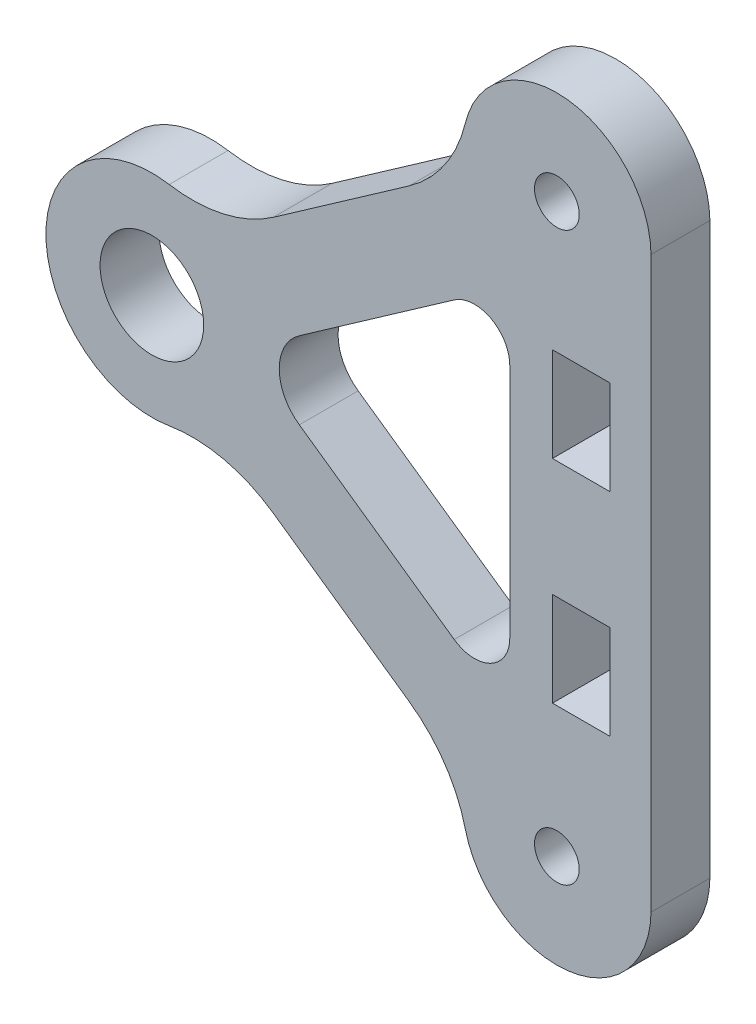
SolidWorks part; units mm, degrees
ref_plane "Plan de face" through (0, 0, 0) normal (0, 0, 1) x (1, 0, 0)
ref_plane "Plan de dessus" through (0, 0, 0) normal (0, 1, 0) x (1, 0, 0)
ref_plane "Plan de droite" through (0, 0, 0) normal (1, 0, 0) x (0, 0, -1)
sketch "Esquisse1" plane through (0, 0, 0) normal (0, 0, 1) x (1, 0, 0)
  line L0 (8.9815, -12.4904) -> (-4.1772, -3.2766)
  line L1 (-4.1772, 3.2766) -> (8.9815, 12.4904)
  line L2 (13.7022, 10.0329) -> (13.7022, -10.0329)
  line L3 (22.2272, 5) -> (17.3272, 5)
  line L4 (17.3272, 5) -> (17.3272, 13)
  line L5 (17.3272, 13) -> (22.2272, 13)
  line L6 (22.2272, 13) -> (22.2272, 5)
  line L7 (22.2272, -13) -> (17.3272, -13)
  line L8 (17.3272, -13) -> (17.3272, -5)
  line L9 (17.3272, -5) -> (22.2272, -5)
  line L10 (22.2272, -5) -> (22.2272, -13)
  line L11 (25.7016, 24.1902) -> (25.7016, -24.1902)
  line L12 (-6.3839, 10.8873) -> (5.1451, 18.96)
  line L13 (5.1451, -18.96) -> (-6.3839, -10.8873)
  arc A0 (5.1451, 18.96) -> (9.9262, 25.97) centre (-1.7378, 28.7898) ccw
  arc A1 (-15.2299, 8.8788) -> (-6.3839, 10.8873) centre (-13.2668, 20.7171) ccw
  arc A2 (-6.3839, -10.8873) -> (-15.2299, -8.8788) centre (-13.2668, -20.7171) ccw
  arc A3 (9.9262, -25.97) -> (5.1451, -18.96) centre (-1.7378, -28.7898) ccw
  arc A4 (8.9815, -12.4904) -> (13.7022, -10.0329) centre (10.7022, -10.0329) ccw
  arc A5 (-4.1772, 3.2766) -> (-4.1772, -3.2766) centre (-1.8829, 0) ccw
  arc A6 (13.7022, 10.0329) -> (8.9815, 12.4904) centre (10.7022, 10.0329) ccw
  circle A7 centre (17.7022, 24.0902) radius 1.9
  circle A8 centre (17.7022, -24.0902) radius 1.9
  arc A9 (25.7016, 24.1902) -> (9.9262, 25.97) centre (17.7022, 24.0902) ccw
  arc A10 (-15.2299, 8.8788) -> (-15.2299, -8.8788) centre (-16.7022, 0) ccw
  arc A11 (9.9262, -25.97) -> (25.7016, -24.1902) centre (17.7022, -24.0902) ccw
  circle A12 centre (-16.7022, 0) radius 4.4
  dimension "D1" = 9
  dimension "D2" = 8
  dimension "D3" = 12
  dimension "D4" = 12
  dimension "D5" = 12
  dimension "D6" = 12
  dimension "D7" = 8
  dimension "D8" = 3.8
  dimension "D9" = 3.8
extrude "Boss.-Extru.1" add sketch "Esquisse1" along normal blind 5
